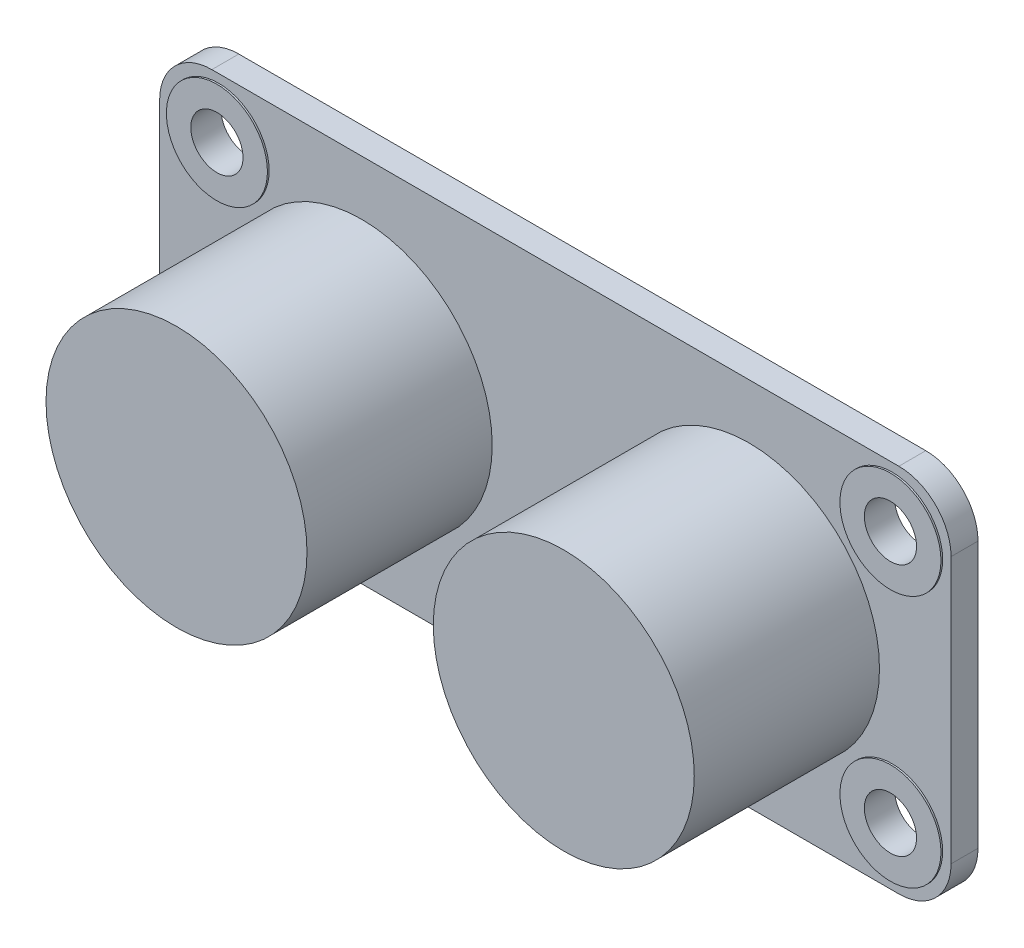
SolidWorks part; units mm, degrees
ref_plane "Front Plane" through (0, 0, 0) normal (0, 0, 1) x (1, 0, 0)
ref_plane "Top Plane" through (0, 0, 0) normal (0, 1, 0) x (1, 0, 0)
ref_plane "Right Plane" through (0, 0, 0) normal (1, 0, 0) x (0, 0, -1)
sketch "Sketch1" plane through (0, 0, 0) normal (0, 0, 1) x (1, 0, 0)
  line L1 (-23.5, -11) -> (23.5, -11)
  line L2 (-23.5, -11) -> (-23.5, 11)
  line L3 (-23.5, 11) -> (23.5, 11)
  line L4 (23.5, -11) -> (23.5, 11)
  line L5 (-23.5, -11) -> (23.5, 11) construction
  line L6 (-23.5, 11) -> (23.5, -11) construction
  circle A0 centre (-20, 7.5) radius 1.55
  circle A1 centre (20, 7.5) radius 1.55
  circle A2 centre (20, -7.5) radius 1.55
  circle A3 centre (-20, -7.5) radius 1.55
  point P0 (0, 0)
  dimension "D3" = 40
  dimension "D5" = 3.1
  dimension "D6" = 3.1
  dimension "D7" = 3.1
  dimension "D8" = 3.1
  dimension "D1" = 47
  dimension "D2" = 22
  dimension "D4" = 15
  dimension "D9" = 7.5
  dimension "D10" = 20
extrude "Boss-Extrude1" add sketch "Sketch1" along normal blind 1.6
fillet "Fillet1" radius 3.1 4 edges at (-23.5, 11, 0.8) (-23.5, -11, 0.8) (23.5, -11, 0.8) (23.5, 11, 0.8)
sketch "Sketch2" plane through (0, 0, 1.6) normal (0, 0, 1) x (1, 0, 0)
  circle A0 centre (-20, 7.5) radius 3
  circle A1 centre (-20, -7.5) radius 3
  circle A2 centre (20, 7.5) radius 3
  circle A3 centre (20, -7.5) radius 3
  circle A4 centre (-20, 7.5) radius 1.55
  circle A5 centre (20, 7.5) radius 1.55
  circle A6 centre (20, -7.5) radius 1.55
  circle A7 centre (-20, -7.5) radius 1.55
  dimension "D1" = 6
  dimension "D2" = 6
  dimension "D3" = 6
  dimension "D4" = 6
  dimension "D5" = 3.1
  dimension "D6" = 3.1
  dimension "D7" = 3.1
  dimension "D8" = 3.1
extrude "Boss-Extrude4" add sketch "Sketch2" along normal blind 0.1 and the other way blind 1.7
sketch "Sketch3" plane through (0, 0, 1.6) normal (0, 0, 1) x (1, 0, 0)
  line L0 (-20.4, -11) -> (20.4, -11) construction
  circle A0 centre (11.5, 0) radius 7.75
  circle A1 centre (-11.5, 0) radius 7.75
  dimension "D1" = 15.5
  dimension "D2" = 15.5
  dimension "D5" = 11
  dimension "D6" = 11
  dimension "D3" = 23
  dimension "D4" = 11.5
extrude "Boss-Extrude8" add sketch "Sketch3" along normal blind 11
